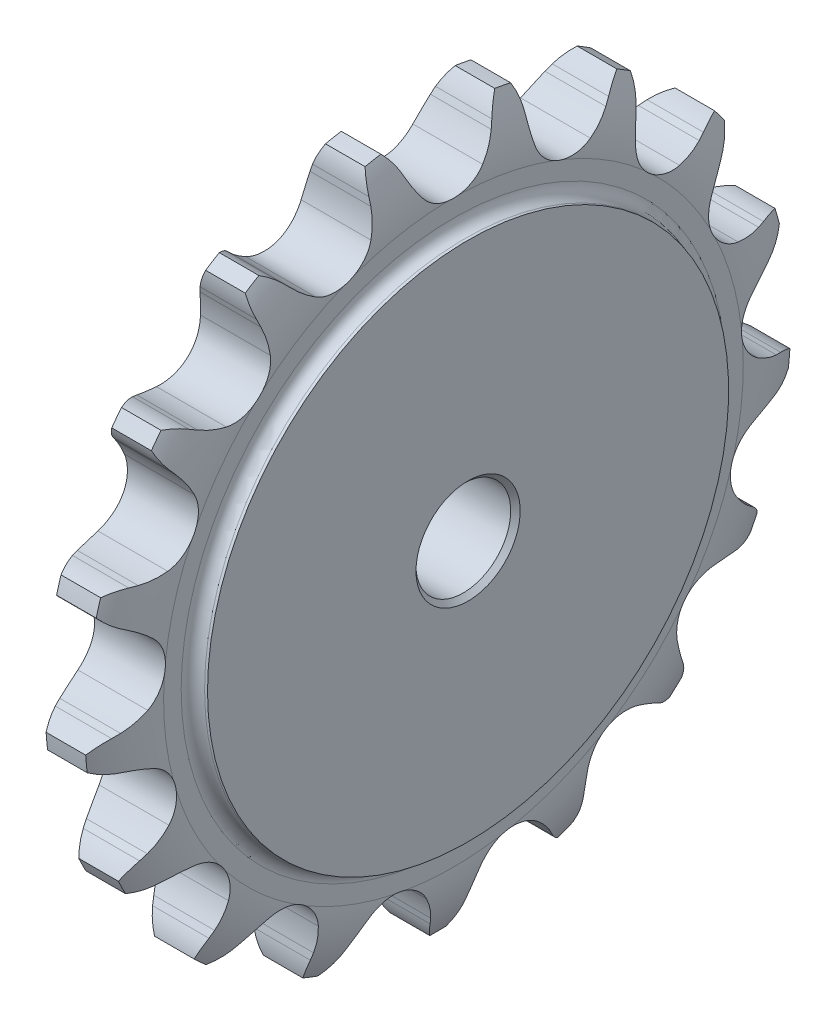
SolidWorks part; units mm, degrees
ref_plane "前视基准面" through (0, 0, 0) normal (0, 0, 1) x (1, 0, 0)
ref_plane "上视基准面" through (0, 0, 0) normal (0, 1, 0) x (1, 0, 0)
ref_plane "右视基准面" through (0, 0, 0) normal (1, 0, 0) x (0, 0, -1)
sketch "草图1" plane through (0, 0, 0) normal (0, 0, 1) x (1, 0, 0)
  line L0 (-12.7, 0) -> (12.7, 0) construction
  line L1 (-10.5692, 10) -> (-10.5692, 55)
  line L2 (-10.5692, 55) -> (-9.9516, 55)
  line L3 (-7.4812, 57.4703) -> (-7.4812, 61.1758)
  line L4 (-4.1792, 74.5) -> (4.1792, 74.5)
  line L5 (7.4812, 61.1758) -> (7.4812, 57.4703)
  line L6 (9.9516, 55) -> (10.5692, 55)
  line L7 (10.5692, 55) -> (10.5692, 10)
  line L8 (10.5692, 10) -> (-10.5692, 10)
  line L9 (0, 0) -> (0, 74.5) construction
  line L10 (-6.463, 69.1158) -> (6.463, 69.1158) construction
  line L11 (-6.463, -69.1158) -> (6.463, -69.1158) construction
  line L12 (12.7, 0) -> (29.7, 0) construction
  line L13 (-7.4812, 61.1758) -> (3.7984, 61.1758) construction
  line L14 (-7.4812, -61.1758) -> (3.7984, -61.1758) construction
  line L15 (29.7, 0) -> (45.58, 0) construction
  line L16 (45.58, 0) -> (69.71, 0) construction
  line L17 (69.71, 0) -> (85.46, 0) construction
  line L18 (85.46, 0) -> (114.75, 0) construction
  arc A0 (-4.1792, 74.5) -> (-7.4812, 61.1758) centre (17.9068, 61.9554) ccw
  arc A1 (4.1792, 74.5) -> (7.4812, 61.1758) centre (-17.9068, 61.9554) cw
  arc A2 (7.4812, 57.4703) -> (9.9516, 55) centre (9.9516, 57.4703) ccw
  arc A3 (-9.9516, 55) -> (-7.4812, 57.4703) centre (-9.9516, 57.4703) ccw
  point P30 (7.4812, 55)
  point P33 (-7.4812, 55)
  dimension "rx" = 25.4
  dimension "D3" = 2.4703
  dimension "d" = 138.2317
  dimension "p" = 25.4
  dimension "z" = 17
  dimension "da" = 149
  dimension "df" = 122.3517
  dimension "dr" = 15.88
  dimension "dk" = 20
  dimension "dg" = 110
  dimension "h" = 24.13
  dimension "bf1" = 14.9625
  dimension "b1" = 15.75
  dimension "ba" = 3.302
  dimension "D2" = 3.0879
  dimension "pt" = 29.29
revolve "旋转1" add sketch "草图1" angle 360 about L0
sketch "草图2" plane through (0, 0, 0) normal (1, 0, 0) x (0, 0, -1)
  line L0 (0, 0) -> (0, 74.5) construction
  line L1 (0, 0) -> (-13.6893, 73.2315) construction
  line L2 (0, 0) -> (-26.9125, 69.4692) construction
  line L3 (6.2815, 64.114) -> (18.1037, 54.7003) construction
  line L4 (9.0289, 68.6546) -> (-9.9382, 77.0294) construction
  line L5 (0, 0) -> (13.6893, 73.2315) construction
  line L6 (9.0289, 68.6546) -> (9.6353, 70.0281)
  line L7 (-9.0289, 68.6546) -> (-9.6353, 70.0281)
  circle A0 centre (0, 0) radius 74.5 construction
  arc A1 (6.2815, 64.114) -> (-6.2815, 64.114) centre (0, 69.1158) cw
  arc A2 (6.2815, 64.114) -> (9.0289, 68.6546) centre (-9.9382, 77.0294) ccw
  arc A3 (12.019, 73.5241) -> (9.6353, 70.0281) centre (20.2925, 65.3225) ccw
  arc A4 (-6.2815, 64.114) -> (-9.0289, 68.6546) centre (9.9382, 77.0294) cw
  arc A5 (-12.019, 73.5241) -> (-9.6353, 70.0281) centre (-20.2925, 65.3225) cw
  arc A7 (12.019, 73.5241) -> (-12.019, 73.5241) centre (0, 0) ccw
  dimension "r1" = 8.0297
  dimension "r3" = 11.6498
  dimension "D1" = 21.176
  dimension "D2" = 10.588
  dimension "α/2" = 51.471
  dimension "M" = 9.9382
  dimension "T" = 7.9135
  dimension "β" = 14.706
  dimension "γ/2" = 13.235
  dimension "bc" = 1.5015
extrude "切除-拉伸1" cut sketch "草图2" against normal mid plane 21.1383
pattern_circular "阵列(圆周)1" count 17 over 360 about axis through (0, 0, 0) along (1, 0, 0) of "切除-拉伸1"
sketch "草图3" plane through (0, 0, 0) normal (0, 0, 1) x (1, 0, 0)
  line L0 (10.5692, 10) -> (4.4308, 10)
  line L3 (4.4308, 10) -> (4.4308, 24.2156)
  line L4 (4.4308, 24.2156) -> (10.5692, 24.2156)
  line L5 (10.5692, 24.2156) -> (10.5692, 10)
  line L6 (0, 0) -> (9.5, 0) construction
  line L8 (-10.5692, 55) -> (-10.5692, -55) construction
  dimension "h" = 14.2156
  dimension "K" = 9.5
  dimension "L" = 15
revolve "旋转2" [suppressed] add sketch "草图3" angle 360 about L6
chamfer "倒角1" distance 1 angle 45 1 edges at (-10.5692, 0, 10)
chamfer "倒角2" distance 1 angle 45 1 edges at (10.5692, 0, 10)
chamfer "倒角3" [suppressed] distance 1 angle 45
scale "缩放比例4" scale about centroid uniform scaling yes scale factor 0.2
ref_plane "基准面1" through (0, 0, 0) normal (-1, 0, 0) x (0, 0, 1)
